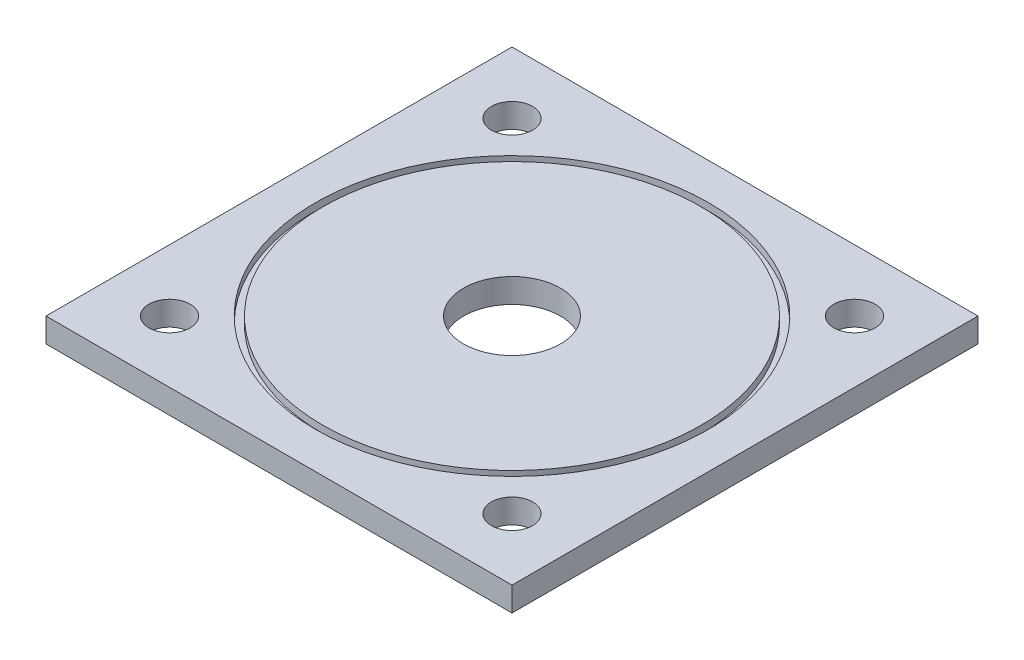
SolidWorks part; units mm, degrees
material "1060 Alloy"
ref_plane "Front" through (0, 0, 0) normal (0, 0, 1) x (1, 0, 0)
ref_plane "Top" through (0, 0, 0) normal (0, 1, 0) x (1, 0, 0)
ref_plane "Right" through (0, 0, 0) normal (1, 0, 0) x (0, 0, -1)
sketch "Sketch1" plane through (0, 0, 0) normal (0, 1, 0) x (1, 0, 0)
  line L1 (-48.1053, 48.1053) -> (48.1053, 48.1053)
  line L2 (-48.1053, 48.1053) -> (-48.1053, -48.1053)
  line L3 (-48.1053, -48.1053) -> (48.1053, -48.1053)
  line L4 (48.1053, 48.1053) -> (48.1053, -48.1053)
  line L5 (-48.1053, 48.1053) -> (48.1053, -48.1053) construction
  line L6 (-48.1053, -48.1053) -> (48.1053, 48.1053) construction
  circle A0 centre (-35.3553, 35.3553) radius 4.25
  circle A1 centre (35.3553, 35.3553) radius 4.25
  circle A2 centre (35.3553, -35.3553) radius 4.25
  circle A3 centre (-35.3553, -35.3553) radius 4.25
  point P0 (0, 0)
  point P17 (0, 0)
  dimension "D3" = 8.5
  dimension "D2" = 50
  dimension "D5" = 50
  dimension "D6" = 50
  dimension "D1" = 12.75
  dimension "D7" = 96.2107
  dimension "D4" = 4
extrude "body extrusion and bolt holes" add sketch "Sketch1" along normal blind 5
sketch "Sketch3" plane through (0, 5, 0) normal (0, 1, 0) x (1, 0, 0)
  circle A0 centre (0, 0) radius 10
  dimension "D1" = 20
extrude "center bore" cut sketch "Sketch3" against normal blind 22.5
sketch "Sketch4" plane through (0, 5, 0) normal (0, 1, 0) x (1, 0, 0)
  circle A0 centre (0, 0) radius 39.8089 construction
  circle A1 centre (0, 0) radius 39.0589
  circle A2 centre (0, 0) radius 40.5589
  dimension "D1" = 79.6178
  dimension "D2" = 0.75
  dimension "D3" = 0.75
extrude "o-ring groove" cut sketch "Sketch4" against normal blind 1.5
sketch "Sketch6" plane through (0, 0, 0) normal (0, -1, 0) x (1, 0, 0)
  circle A0 centre (0, 0) radius 39.0589 construction
  circle A1 centre (0, 0) radius 39.0589
  circle A2 centre (0, 0) radius 40.5589
  circle A3 centre (0, 0) radius 40.5589 construction
extrude "Cut-Extrude2" cut sketch "Sketch6" against normal blind 1.5
equation "\"motor mount pattern diameter\"= 30mm"
equation "\"D2@Sketch1\" = \"motor mount to housing m8 pattern diameter\" / 2"
equation "\"D3@Sketch1\" = \"motor mount to housing m8 screw hole diameter\""
equation "\"D5@Sketch1\" = \"motor mount to housing m8 pattern diameter\" / 2"
equation "\"D6@Sketch1\" = \"motor mount to housing m8 pattern diameter\" / 2"
equation "\"D1@Sketch1\" = \"motor mount to housing m8 screw post radius\""
equation "\"D1@body extrusion and bolt holes\"=\"impeller boss depth\""
equation "\"D1@Sketch3\"=\"impeller boss diameter\"+4mm"
equation "\"D1@center bore\" = \"housing top total thickness\""
equation "\"bearing OD\" = 20mm"
equation "\"bearing outer race thickness\"= 1mm"
equation "\"bearing ID\"= 10mm"
equation "\"bearing depth\"= 6mm"
equation "\"bearing inner race thickness\"= 1mm"
equation "\"seal OD\" = 20mm"
equation "\"seal ID\"= 8mm"
equation "\"seal depth\"= 6mm"
equation "\"impeller base outer diameter\"= 1.75in"
equation "\"impeller base outer thickness\"= 1mm"
equation "\"impeller base center thickness\"= 5mm"
equation "\"impeller number of vanes\"= 8"
equation "\"impeller vane inner height\"= 8mm"
equation "\"impeller primary vane opening diamater\"= 10mm"
equation "\"impeller vane inner thickness\"= .75mm"
equation "\"impeller vane outer thickness\"= 1.5mm"
equation "\"impeller primary vane entrance angle\"= 20deg"
equation "\"impeller secondary vane entrance angle\"= 20deg"
equation "\"impeller secondary vane opening diameter\"= 10mm"
equation "\"motor to housing distance\"= 60mm"
equation "\"motor mount coupler shaft hole diameter\"= \"coupler shaft base diameter\"+ 4mm"
equation "\"motor mount to housing m8 screw hole diameter\"= 8.5mm"
equation "\"motor mount to housing m8 screw post radius\"= ( 3 * \"motor mount to housing m8 screw hole diameter\" ) / 2"
equation "\"motor mount to housing m8 pattern diameter\"= 100mm"
equation "\"motor mount to housing m4 screw hole diamater\"= 4mm"
equation "\"motor mount to housing m4 head diameter\"= 7.25mm"
equation "\"motor mount to housing m4 head depth\"= 4mm"
equation "\"motor mount plate thickness\"= 6mm + \"motor mount to housing m4 head depth\""
equation "\"housing bearing seat lip thickness\" = 2mm"
equation "\"housing base thickness\"= \"housing bearing seat lip thickness\" + \"seal depth\" + \"bearing depth\""
equation "\"housing top impeller vertical clearance\"= .5mm"
equation "\"housing top impeller horizontal clearance\"= .5mm"
equation "\"housing top impeller bottom clearance\"= 1mm"
equation "\"housing top impeller cavity height\"= \"housing top impeller bottom clearance\" + \"impeller base center thickness\" + \"impeller vane inner height\" + \"housing top impeller vertical clearance\""
equation "\"housing top impeller cavity diameter\"= 2 * \"housing top impeller horizontal clearance\" + \"impeller base outer diameter\""
equation "\"housing top impeller cavity tip height\"= \"housing top impeller bottom clearance\" + \"housing top impeller vertical clearance\" + \"impeller base outer thickness\" + \"impeller vane outer height\""
equation "\"housing top entrance OD\"= 20mm"
equation "\"housing top exit OD\"= 5mm"
equation "\"housing top o-ring channel height\"= 1.5mm"
equation "\"housing top o ring channel width\"= 1.5mm"
equation "\"housing top threaded inlet depth\"= 8mm"
equation "\"housing top total thickness\"= \"housing top threaded inlet depth\" + \"housing top impeller cavity height\""
equation "\"housing top total width\"= 10mm"
equation "\"housing top exit threaded diameter\"= 8mm"
equation "\"housing top exit threaded depth\"= 8mm"
equation "\"motor shaft pride\"= 32mm"
equation "\"motor shaft flat section length from tip\"= 25.7mm"
equation "\"motor shaft bore end clearance\"= 2mm"
equation "\"motor mount shaft hole depth\"= \"motor shaft pride\""
equation "\"coupler shaft set screw drill hole diameter\"= 6mm"
equation "\"coupler shaft set screw 1 distance\"= \"motor mount shaft hole depth\" / 3"
equation "\"coupler shaft set screw 2 distance\"= \"motor mount shaft hole depth\" * 4 / 5"
equation "\"coupler shaft motor shaft hole diameter\"= 8mm"
equation "\"coupler shaft base diameter\"= 18mm"
equation "\"coupler shaft base length\"= \"motor mount shaft hole depth\" + 10mm"
equation "\"coupler shaft second section diameter\"= \"bearing ID\" + \"bearing inner race thickness\" * 2"
equation "\"coupler shaft second section length\"= \"motor to housing distance\" -  \"coupler shaft base length\" - 2mm"
equation "\"coupler shaft third section diamater\"= \"bearing ID\""
equation "\"coupler shaft third section length\"= \"bearing depth\""
equation "\"coupler shaft seal section diameter\" = \"seal ID\""
equation "\"coupler shaft seal section length\" = \"housing base thickness\"+\"housing top impeller bottom clearance\"-\"bearing depth\""
equation "\"coupler shaft impeller section diameter\" = 6mm"
equation "\"coupler shaft impeller section length\" = \"impeller boss depth\"+\"impeller base center thickness\" - 1mm"
equation "\"coupler shaft impeller screw hole diameter\" = \"motor mount to housing m4 screw hole diamater\""
equation "\"coupler shaft impeller screw hole depth\" = 10mm"
equation "\"housing top o-ring circumference\" = 250mm"
equation "\"housing top o-ring radius\" = (\"housing top o-ring circumference\")/(2*3.14)"
equation "\"impeller vane outer height\"= 4mm"
equation "\"impeller bolt surface height\" = 5mm"
equation "\"impeller bolt surface diameter\" = 8mm"
equation "\"impeller boss depth\" = 5mm"
equation "\"impeller dowel diameter\" = 2mm"
equation "\"coupler shaft to motor clearance\" = 2mm"
equation "\"impeller boss diameter\" = \"coupler shaft impeller section diameter\"+2*5mm"
equation "\"impeller dowel length\" = 2mm*2 + \"coupler shaft impeller section diameter\""
equation "\"D1@Sketch4\"=\"housing top o-ring radius\"*2"
equation "\"D2@Sketch4\"=\"housing top o ring channel width\"/2"
equation "\"D3@Sketch4\"=\"housing top o ring channel width\"/2"
equation "\"housing top o ring channel depth\"=10"
equation "\"D1@o-ring groove\" = \"housing top o-ring channel height\""
equation "\"D1@Cut-Extrude2\"=\"housing top o-ring channel height\""
